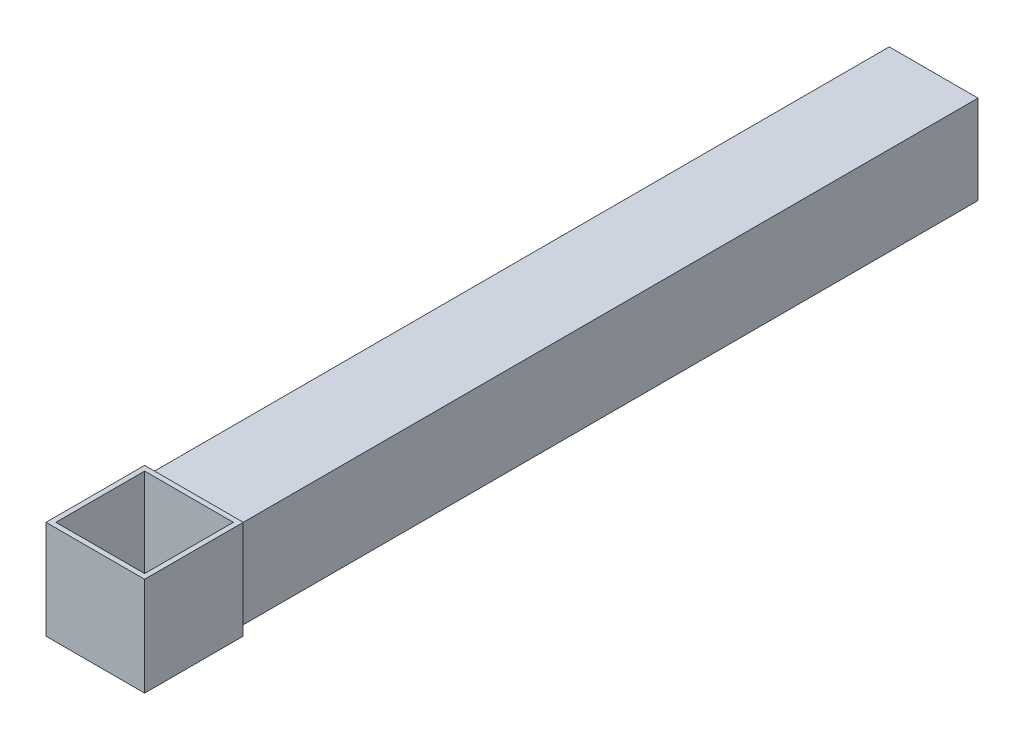
SolidWorks part; units mm, degrees
ref_plane "Front Plane" through (0, 0, 0) normal (0, 0, 1) x (1, 0, 0)
ref_plane "Top Plane" through (0, 0, 0) normal (0, 1, 0) x (1, 0, 0)
ref_plane "Right Plane" through (0, 0, 0) normal (1, 0, 0) x (0, 0, -1)
sketch "Sketch1" plane through (0, 0, 0) normal (0, 0, 1) x (1, 0, 0)
  line L1 (-18, -18) -> (18, -18)
  line L2 (-18, -18) -> (-18, 18)
  line L3 (-18, 18) -> (18, 18)
  line L4 (18, -18) -> (18, 18)
  line L5 (-18, -18) -> (18, 18) construction
  line L6 (-18, 18) -> (18, -18) construction
  point P0 (0, 0)
  dimension "D1" = 36
extrude "Boss-Extrude1" add sketch "Sketch1" along normal blind 300
sketch "Sketch2" plane through (0, 0, 0) normal (0, 1, 0) x (1, 0, 0)
  line L0 (18, -300) -> (-18, -300) construction
  line L1 (-20, -340) -> (20, -340)
  line L2 (-20, -340) -> (-20, -300)
  line L3 (-20, -300) -> (20, -300)
  line L4 (20, -340) -> (20, -300)
  line L6 (-18, -338) -> (18, -338)
  line L7 (-18, -338) -> (-18, -302)
  line L8 (-18, -302) -> (18, -302)
  line L9 (18, -338) -> (18, -302)
  line L10 (-18, -338) -> (18, -302) construction
  line L11 (-18, -302) -> (18, -338) construction
  point P4 (0, -340)
  point P8 (0, -320)
  point P13 (0, 0)
  dimension "D1" = 40
  dimension "D2" = 40
  dimension "D3" = 2
  dimension "D4" = 2
extrude "Boss-Extrude2" add sketch "Sketch2" along normal blind 20 and the other way blind 20
